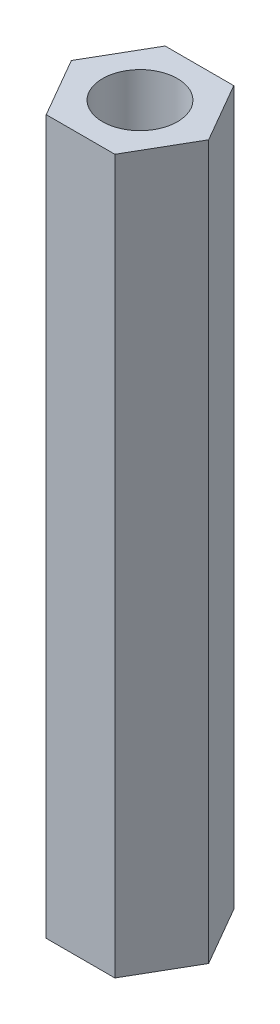
SolidWorks part; units mm, degrees
ref_plane "Спереди" through (0, 0, 0) normal (0, 0, 1) x (1, 0, 0)
ref_plane "Сверху" through (0, 0, 0) normal (0, 1, 0) x (1, 0, 0)
ref_plane "Справа" through (0, 0, 0) normal (1, 0, 0) x (0, 0, -1)
sketch "Эскиз1" plane through (0, 0, 0) normal (0, 1, 0) x (1, 0, 0)
  line L1 (2.8868, 0) -> (1.4434, 2.5)
  line L2 (1.4434, 2.5) -> (-1.4434, 2.5)
  line L3 (-1.4434, 2.5) -> (-2.8868, 0)
  line L4 (-2.8868, 0) -> (-1.4434, -2.5)
  line L5 (-1.4434, -2.5) -> (1.4434, -2.5)
  line L6 (1.4434, -2.5) -> (2.8868, 0)
  circle A0 centre (0, 0) radius 2.5 construction
  dimension "D1" = 5
extrude "Бобышка-Вытянуть1" add sketch "Эскиз1" along normal blind 30
hole_wizard "Сверло под метчик  спиральное M35" positions "Эскиз16" profile "Эскиз17" hole size "M3x0.5" standard "DIN"
sketch "Эскиз16" plane through (0, 30, 0) normal (0, 1, 0) x (1, 0, 0)
  point P0 (0, 0)
sketch "Эскиз17" plane through (0, 30, 0) normal (1, 0, 0) x (0, 0, 1)
  line L0 (0, 0) -> (0, 8.9464)
  line L1 (0, 8.9464) -> (1.575, 8)
  line L2 (1.575, 8) -> (1.575, 0)
  line L5 (1.575, 0) -> (0, 0)
  line L10 (0, 8.9464) -> (-1.575, 8) construction
  line L11 (0, -6.35) -> (0, 107.95) construction
  dimension "Диаметр отверстия" = 3.15
  dimension "Глубина отверстия" = 8
  dimension "Угол заточки сверла" = 118
hole_wizard "Сверло под метчик  спиральное M36" positions "Эскиз18" profile "Эскиз19" hole size "M3x0.5" standard "DIN"
sketch "Эскиз18" plane through (0, 0, 0) normal (0, -1, 0) x (-1, 0, 0)
  point P0 (0, 0)
sketch "Эскиз19" plane through (0, 0, 0) normal (1, 0, 0) x (0, 0, -1)
  line L0 (0, 0) -> (0, 8.9464)
  line L1 (0, 8.9464) -> (1.575, 8)
  line L2 (1.575, 8) -> (1.575, 0)
  line L5 (1.575, 0) -> (0, 0)
  line L10 (0, 8.9464) -> (-1.575, 8) construction
  line L11 (0, -6.35) -> (0, 107.95) construction
  dimension "Диаметр отверстия" = 3.15
  dimension "Глубина отверстия" = 8
  dimension "Угол заточки сверла" = 118
